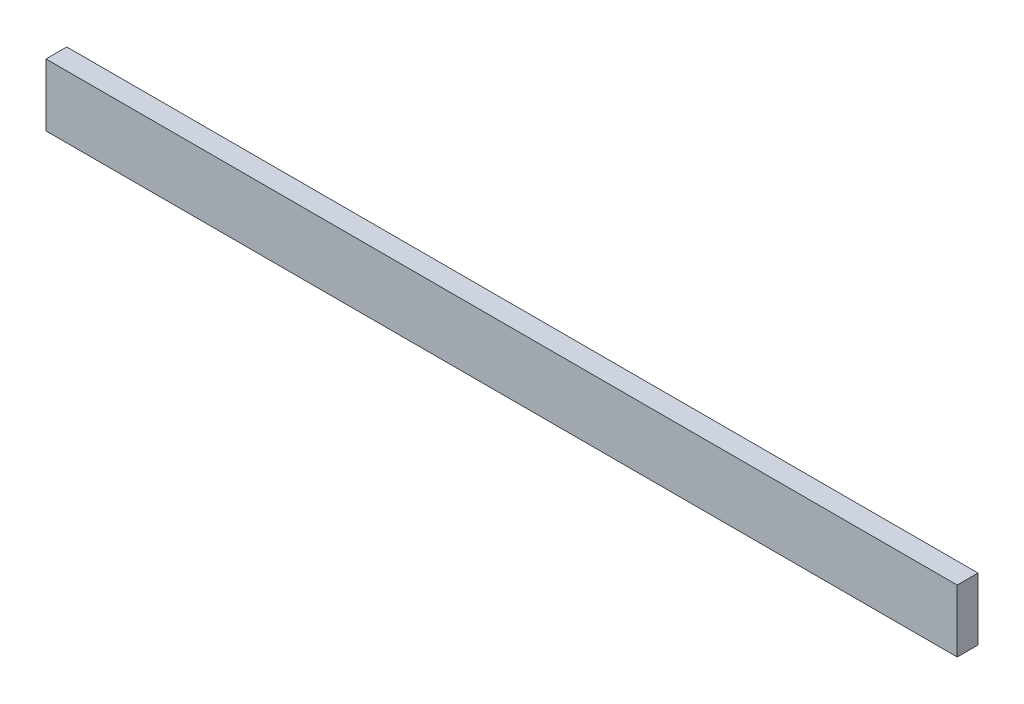
SolidWorks part; units mm, degrees
ref_plane "Front Plane" through (0, 0, 0) normal (0, 0, 1) x (1, 0, 0)
ref_plane "Top Plane" through (0, 0, 0) normal (0, 1, 0) x (1, 0, 0)
ref_plane "Right Plane" through (0, 0, 0) normal (1, 0, 0) x (0, 0, -1)
sketch "Sketch1" plane through (0, 0, 0) normal (0, 0, 1) x (1, 0, 0)
  line L1 (0, 0) -> (278.384, 0)
  line L2 (0, 0) -> (0, 19.05)
  line L3 (0, 19.05) -> (278.384, 19.05)
  line L4 (278.384, 0) -> (278.384, 19.05)
  dimension "D1" = 278.384
  dimension "D2" = 19.05
extrude "Boss-Extrude1" add sketch "Sketch1" along normal blind 6.35
